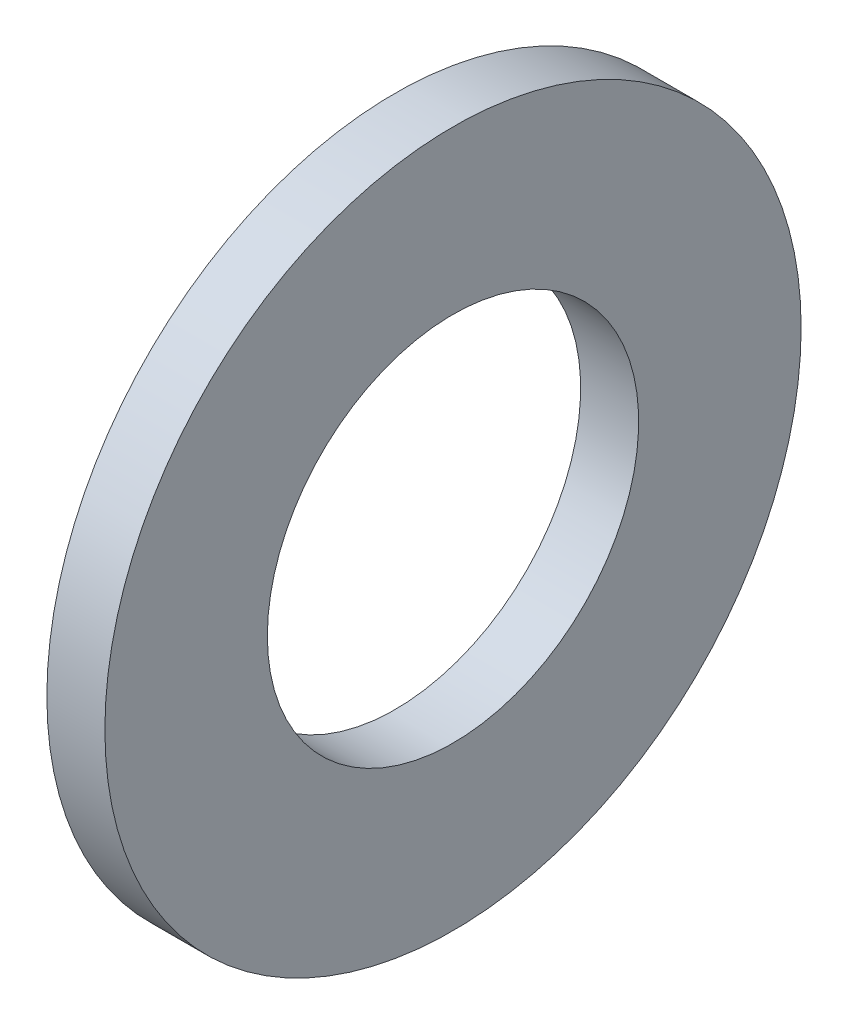
SolidWorks part; units mm, degrees
ref_plane "Plane1" through (0, 0, 0) normal (0, 0, 1) x (1, 0, 0)
ref_plane "Plane2" through (0, 0, 0) normal (0, 1, 0) x (1, 0, 0)
ref_plane "Plane3" through (0, 0, 0) normal (1, 0, 0) x (0, 0, -1)
sketch "Sketch1" plane through (0, 0, 0) normal (0, 0, 1) x (1, 0, 0)
  line L0 (-34.925, 0) -> (9.525, 0) construction
  line L1 (0, 3.2) -> (0, 6)
  line L2 (0, 6) -> (-1, 6)
  line L3 (-1, 6) -> (-1, 3.2)
  line L4 (-1, 3.2) -> (0, 3.2)
  dimension "Thickness" = 1
  dimension "Inside_dia" = 6.4
  dimension "Outside_dia" = 12
revolve "Base-Revolve" add sketch "Sketch1" angle 360 about L0
